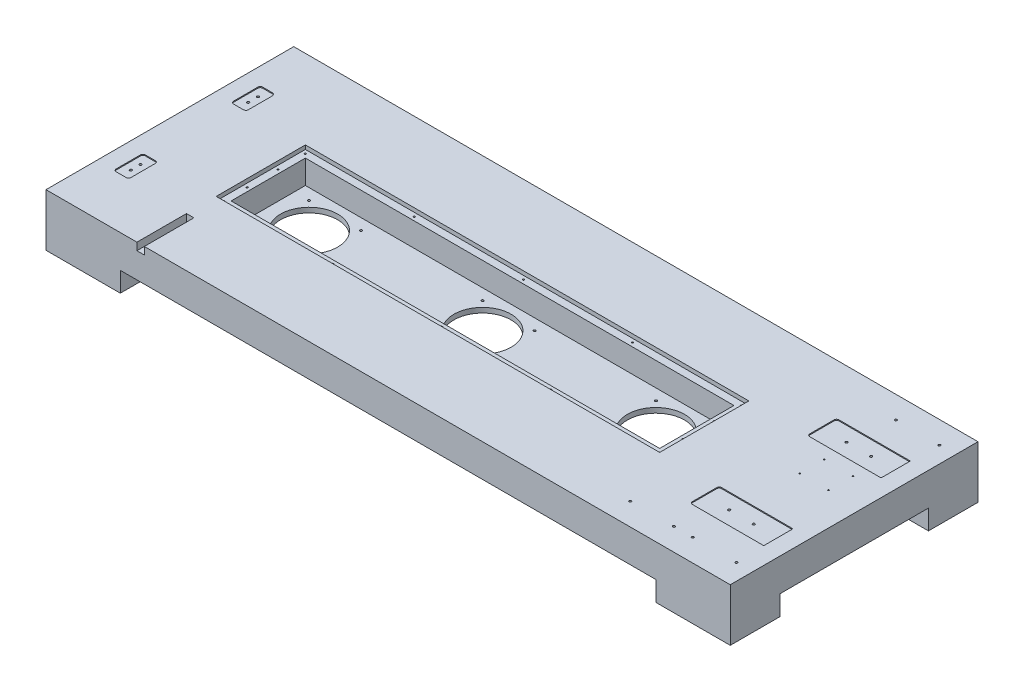
SolidWorks part; units mm, degrees
ref_plane "Front Plane" through (0, 0, 0) normal (0, 0, 1) x (1, 0, 0)
ref_plane "Top Plane" through (0, 0, 0) normal (0, 1, 0) x (1, 0, 0)
ref_plane "Right Plane" through (0, 0, 0) normal (1, 0, 0) x (0, 0, -1)
sketch "Sketch1" plane through (0, 0, 0) normal (0, 1, 0) x (1, 0, 0)
  line L1 (-750, 250) -> (750, 250)
  line L2 (-750, 250) -> (-750, -250)
  line L3 (-750, -250) -> (750, -250)
  line L4 (750, 250) -> (750, -250)
  line L5 (-750, 250) -> (750, -250) construction
  line L6 (-750, -250) -> (750, 250) construction
  point P0 (0, 0)
  dimension "D1" = 1500
  dimension "D2" = 500
sketch "Sketch19" plane through (0, 0, 0) normal (0, 1, 0) x (1, 0, 0)
  line L2 (-447.5, 90) -> (-447.5, -90)
  line L4 (-432.5, 75) -> (-432.5, -75)
  line L6 (-432.5, -75) -> (432.5, -75)
  line L8 (-447.5, -90) -> (447.5, -90)
  line L10 (-447.5, 90) -> (447.5, 90)
  line L12 (-432.5, 75) -> (432.5, 75)
  line L14 (0, 90) -> (0, -90) construction
  line L16 (432.5, 75) -> (432.5, -75)
  line L18 (447.5, 90) -> (447.5, -90)
  point P3 (-432.5, 0)
  dimension "D1" = 15
  dimension "D2" = 15
  dimension "D3" = 15
  dimension "D4" = 15
  dimension "D5" = 865
  dimension "D6" = 150
extrude "Boss-Extrude2" add sketch "Sketch19" along normal blind 48 separate body
sketch "Sketch22" plane through (0, 0, 0) normal (0, 1, 0) x (1, 0, 0)
  line L1 (-447.5, 90) -> (447.5, 90)
  line L2 (-447.5, 90) -> (-447.5, -90)
  line L3 (-447.5, -90) -> (447.5, -90)
  line L4 (447.5, 90) -> (447.5, -90)
  line L5 (-447.5, 90) -> (447.5, -90) construction
  line L6 (-447.5, -90) -> (447.5, 90) construction
extrude "Boss-Extrude3" add sketch "Sketch22" against normal blind 10
sketch "Sketch23" plane through (0, 0, 0) normal (0, 1, 0) x (1, 0, 0)
  line L0 (-447.5, -90) -> (447.5, -90) construction
  line L1 (-750, 250) -> (750, 250)
  line L2 (-750, 250) -> (-750, -250)
  line L3 (-750, -250) -> (750, -250)
  line L4 (750, 250) -> (750, -250)
  line L5 (-447.5, 90) -> (-447.5, -90) construction
  line L6 (447.5, 90) -> (-447.5, 90) construction
  line L7 (447.5, -90) -> (447.5, 90) construction
  line L8 (-447.5, -90) -> (447.5, -90)
  line L9 (-447.5, 90) -> (-447.5, -90)
  line L10 (447.5, 90) -> (-447.5, 90)
  line L11 (447.5, -90) -> (447.5, 90)
extrude "Boss-Extrude4" add sketch "Sketch23" along normal offset from surface 8 and the other way up to surface (10 mm away) up to face at (0, 48, 0) offset beyond the face yes other way up to face at (0, -10, 0)
sketch "Sketch25" plane through (0, 0, 0) normal (0, -1, 0) x (1, 0, 0)
  line L0 (376.7104, 95) -> (506.8132, 123.2951) construction
  line L1 (376.7104, 133.9838) -> (510.7651, 84.6333) construction
  line L6 (-447.5, 90) -> (447.5, 90) construction
  line L8 (521.7058, 80.9826) -> (521.6427, 137.9826)
  line L9 (376.7104, 90) -> (520.9741, 90)
  line L10 (371.7104, 133.9838) -> (371.7104, 95)
  line L11 (520.6818, 138.8932) -> (376.6818, 138.9837)
  arc A0 (371.7104, 95) -> (376.7104, 90) centre (376.7104, 95) ccw
  arc A8 (520.9741, 90) -> (521.7058, 80.9826) centre (510.7651, 84.6333) ccw
  arc A10 (376.6818, 138.9837) -> (371.7104, 133.9838) centre (376.7104, 133.9838) ccw
  arc A11 (521.6427, 137.9826) -> (520.6818, 138.8932) centre (506.8132, 123.2951) ccw
  point P2 (443.2788, 109.4775)
  dimension "D5" = 5
  dimension "D2" = 5
  dimension "D1" = 144
  dimension "D4" = 57
sketch "Sketch26" plane through (0, 0, 0) normal (0, 1, 0) x (1, 0, 0)
  line L0 (-432.5, -75) -> (-447.5, -90) construction
  line L1 (-447.5, 90) -> (-432.5, 75) construction
  line L2 (432.5, -75) -> (447.5, -90) construction
  line L5 (432.5, 75) -> (447.5, 90) construction
  circle A2 centre (-440, -82.5) radius 1.65
  circle A3 centre (-440, 82.5) radius 1.65
  point P4 (-440, -82.5)
  point P15 (440, -82.5)
  point P16 (440, 82.5)
  dimension "D1" = 3.3
  dimension "D3" = 3.3
extrude "Cut-Extrude6" cut sketch "Sketch26" against normal blind 20 from surface at 48 starting at face at (0, 48, 0)
pattern_linear "LPattern1" count 5 spacing 220 along (1, 0, 0) of "Cut-Extrude6"
sketch "Sketch27" plane through (0, 0, 0) normal (0, 1, 0) x (1, 0, 0)
  line L0 (-432.5, 0) -> (-447.5, 0) construction
  line L1 (-432.5, 75) -> (-432.5, -75) construction
  line L2 (-447.5, -90) -> (-447.5, 90) construction
  line L3 (0, -55) -> (0, 55) construction
  line L6 (-440, 90) -> (-440, -90) construction
  line L7 (-447.5, 90) -> (447.5, 90) construction
  line L8 (-447.5, -90) -> (447.5, -90) construction
  line L9 (-504.8814, 84.3322) -> (-440, 84.15) construction
  line L10 (-440, 84.15) -> (-440, 90) construction
  line L11 (440, 84.15) -> (440, 90) construction
  line L12 (504.8814, 84.3322) -> (440, 84.15) construction
  line L13 (440, 90) -> (440, -90) construction
  line L14 (432.5, 0) -> (447.5, 0) construction
  circle A2 centre (-440, 27.5) radius 1.65
  circle A3 centre (-440, -35) radius 1.65
  circle A4 centre (-440, 82.5) radius 1.65 construction
  circle A5 centre (-440, 82.5) radius 1.65 construction
  circle A6 centre (440, -35) radius 1.65
  circle A7 centre (440, 27.5) radius 1.65
  dimension "D5" = 3.3
  dimension "D6" = 3.3
  dimension "D3" = 62.5
  dimension "D4" = 62.5
sketch "Sketch28" plane through (0, 0, 0) normal (0, 1, 0) x (1, 0, 0)
  line L0 (0, 0) -> (57.7, 0) construction
  line L1 (-52.5, 52.5) -> (52.5, 52.5) construction
  line L2 (-52.5, 52.5) -> (-52.5, -52.5) construction
  line L3 (-52.5, -52.5) -> (52.5, -52.5) construction
  line L4 (52.5, 52.5) -> (52.5, -52.5) construction
  line L5 (-52.5, 52.5) -> (52.5, -52.5) construction
  line L6 (-52.5, -52.5) -> (52.5, 52.5) construction
  circle A0 centre (-52.5, 52.5) radius 2.3
  circle A1 centre (52.5, 52.5) radius 2.3
  circle A2 centre (52.5, -52.5) radius 2.3
  circle A3 centre (-52.5, -52.5) radius 2.3
  circle A4 centre (0, 0) radius 57.7
  point P2 (0, 0)
  dimension "D3" = 4.6
  dimension "D4" = 4.6
  dimension "D5" = 4.6
  dimension "D6" = 4.6
  dimension "D7" = 57.7
  dimension "D1" = 105
  dimension "D2" = 105
extrude "Cut-Extrude7" cut sketch "Sketch28" against normal through all both and the other way through all
pattern_linear "LPattern2" count 2 spacing 350 along (-1, 0, 0) count 2 spacing 350 along (1, 0, 0) of "Cut-Extrude7"
extrude "Cut-Extrude8" cut sketch "Sketch27" against normal blind 20 from surface at 48 starting at face at (220, 48, -84.15)
sketch "Sketch30" plane through (0, 0, 0) normal (0, -1, 0) x (1, 0, 0)
  line L0 (566.5, -147.92) -> (715.5, -88.92) construction
  line L1 (566.5, -88.92) -> (715.5, -147.92) construction
  line L2 (566.5, -93.92) -> (566.5, -88.92) construction
  line L3 (566.5, -88.92) -> (571.5, -88.92) construction
  line L4 (571.5, -147.92) -> (566.5, -147.92) construction
  line L5 (566.5, -147.92) -> (566.5, -142.92) construction
  line L6 (571.5, -147.92) -> (714.5, -147.92)
  line L7 (0, 0) -> (750, 0) construction
  line L8 (715.5, -146.92) -> (715.5, -89.92)
  line L10 (566.5, -93.92) -> (566.5, -142.92)
  line L11 (714.5, -88.92) -> (571.5, -88.92)
  line L12 (750, -250) -> (750, 250) construction
  line L14 (0, 0) -> (0, -118.42) construction
  line L15 (566.5, -118.42) -> (0, -118.42) construction
  arc A0 (715.5, -89.92) -> (714.5, -88.92) centre (714.5, -89.92) ccw
  arc A1 (714.5, -147.92) -> (715.5, -146.92) centre (714.5, -146.92) ccw
  arc A9 (566.5, -142.92) -> (571.5, -147.92) centre (571.5, -142.92) ccw
  arc A10 (571.5, -88.92) -> (566.5, -93.92) centre (571.5, -93.92) ccw
  dimension "D1" = 5
  dimension "D2" = 5
  dimension "D5" = 88.92
  dimension "D6" = 566.5
  dimension "D3" = 1
  dimension "D4" = 49
  dimension "D8" = 144
extrude "Cut-Extrude9" cut sketch "Sketch30" along normal blind 2 from surface at -56 starting at face at (0, 56, 0)
mirror "Mirror1" about plane through (0, 0, 0) normal (0, 0, 1) of "Cut-Extrude9"
sketch "Sketch32" plane through (0, 0, 0) normal (0, 1, 0) x (1, 0, 0)
  line L4 (-566.5, 118.42) -> (566.5, 118.42) construction
  line L5 (-591.5, 147.92) -> (-571.5, 147.92)
  line L6 (-596.5, 142.92) -> (-596.5, 93.92)
  line L7 (-591.5, 88.92) -> (-571.5, 88.92)
  line L8 (-566.5, 142.92) -> (-566.5, 93.92)
  line L9 (566.5, 93.92) -> (566.5, 142.92) construction
  arc A4 (-566.5, 142.92) -> (-571.5, 147.92) centre (-571.5, 142.92) ccw
  arc A5 (-566.5, 93.92) -> (-571.5, 88.92) centre (-571.5, 93.92) cw
  arc A6 (-596.5, 93.92) -> (-591.5, 88.92) centre (-591.5, 93.92) ccw
  arc A7 (-596.5, 142.92) -> (-591.5, 147.92) centre (-591.5, 142.92) cw
  point P6 (-566.5, 147.92)
  point P11 (-596.5, 88.92)
  point P14 (-596.5, 147.92)
  dimension "D2" = 20
  dimension "D3" = 5
  dimension "D1" = 49
  dimension "D4" = 1133
extrude "Cut-Extrude10" cut sketch "Sketch32" against normal blind 2 from surface at 56 starting at face at (0, 56, 0)
mirror "Mirror2" about plane through (0, 0, 0) normal (0, 0, 1) of "Cut-Extrude10"
sketch "Sketch33" plane through (0, 0, 0) normal (0, 1, 0) x (1, 0, 0)
  line L0 (-581.5, 147.92) -> (-581.5, 88.92) construction
  line L1 (-571.5, 147.92) -> (-591.5, 147.92) construction
  line L2 (-591.5, 88.92) -> (-571.5, 88.92) construction
  line L3 (-581.5, -88.92) -> (-581.5, -147.92) construction
  line L4 (-591.5, -88.92) -> (-571.5, -88.92) construction
  line L5 (-571.5, -147.92) -> (-591.5, -147.92) construction
  line L6 (566.5, 118.42) -> (715.5, 118.42) construction
  line L7 (566.5, 93.92) -> (566.5, 142.92) construction
  line L8 (715.5, 146.92) -> (715.5, 89.92) construction
  line L9 (566.5, -118.42) -> (715.5, -118.42) construction
  line L10 (566.5, -93.92) -> (566.5, -142.92) construction
  line L11 (715.5, -146.92) -> (715.5, -89.92) construction
  circle A0 centre (-581.5, 108.58) radius 2.35
  circle A1 centre (-581.5, -108.59) radius 2.35
  circle A2 centre (-581.5, 128.25) radius 2.35
  circle A3 centre (-581.5, -128.26) radius 2.35
  circle A4 centre (616.17, -118.42) radius 2.35
  circle A5 centre (665.84, -118.42) radius 2.35
  circle A6 centre (616.17, 118.42) radius 2.35
  circle A7 centre (665.84, 118.42) radius 2.35
  dimension "D1" = 4.7
  dimension "D2" = 4.7
  dimension "D3" = 4.7
  dimension "D8" = 4.7
  dimension "D11" = 4.7
  dimension "D12" = 4.7
  dimension "D13" = 4.7
  dimension "D14" = 4.7
  dimension "D4" = 19.67
  dimension "D5" = 19.67
  dimension "D6" = 19.67
  dimension "D7" = 19.67
  dimension "D9" = 49.67
  dimension "D10" = 49.67
extrude "Cut-Extrude11" cut sketch "Sketch33" against normal through all both and the other way through all
sketch "Sketch34" plane through (0, 0, 0) normal (0, 1, 0) x (1, 0, 0)
  line L0 (-596.5, -118.42) -> (-631, -118.42) construction
  line L1 (-596.5, -142.92) -> (-596.5, -93.92) construction
  line L2 (750, -250) -> (-750, -250) construction
  line L3 (-631, -250) -> (-821.8308, -250)
  line L4 (-631, -250) -> (-631, 290.53)
  line L5 (-631, 290.53) -> (-821.8308, 290.53)
  line L6 (-821.8308, -250) -> (-821.8308, 290.53)
  dimension "D1" = 34.5
extrude "Cut-Extrude12" cut sketch "Sketch34" along normal through all both and the other way through all
sketch "Sketch29" plane through (0, 0, 0) normal (0, 1, 0) x (1, 0, 0)
  line L1 (-631, -250) -> (-481, -250)
  line L2 (-631, -250) -> (-631, -150)
  line L3 (-631, -150) -> (-481, -150)
  line L4 (-481, -250) -> (-481, -150)
  line L5 (-631, 250) -> (-481, 250)
  line L6 (-631, 250) -> (-631, 150)
  line L7 (-631, 150) -> (-481, 150)
  line L8 (-481, 250) -> (-481, 150)
  line L9 (750, -250) -> (600, -250)
  line L10 (750, -250) -> (750, -150)
  line L11 (750, -150) -> (600, -150)
  line L12 (600, -250) -> (600, -150)
  line L13 (750, 250) -> (600, 250)
  line L14 (750, 250) -> (750, 150)
  line L15 (750, 150) -> (600, 150)
  line L16 (600, 250) -> (600, 150)
  dimension "D1" = 150
  dimension "D2" = 100
  dimension "D3" = 150
  dimension "D4" = 100
  dimension "D5" = 150
  dimension "D6" = 100
  dimension "D7" = 100
  dimension "D8" = 150
extrude "Boss-Extrude5" add sketch "Sketch29" against normal blind 50
sketch "Sketch35" plane through (0, 0, 0) normal (0, 1, 0) x (1, 0, 0)
  line L0 (750, -250) -> (-631, -250) construction
  line L1 (-447.5, 90) -> (-432.5, 90) construction
  line L2 (-447.5, 90) -> (-447.5, -250) construction
  line L3 (-447.5, -250) -> (-432.5, -250) construction
  line L4 (-432.5, 90) -> (-432.5, -250) construction
  line L5 (-447.5, 90) -> (447.5, 90) construction
  line L6 (447.5, 90) -> (447.5, 75.0032) construction
  line L7 (447.5, 90) -> (447.5, -90) construction
  line L8 (447.5, 75.0032) -> (-447.5, 75.0032) construction
  line L10 (-447.5, -250) -> (-432.5, -250)
  line L11 (-447.5, -250) -> (-447.5, -150)
  line L12 (-447.5, -150) -> (-432.5, -150)
  line L13 (-432.5, -250) -> (-432.5, -150)
  dimension "D1" = 15
  dimension "D2" = 14.9968
  dimension "D3" = 100
extrude "Cut-Extrude13" cut sketch "Sketch35" against normal blind 15 from surface at 56 starting at face at (-581.5, 56, -118.42)
sketch "Sketch36" plane through (0, 56, 0) normal (0, 1, 0) x (-1, 0, 0)
  line L0 (-750, -250) -> (-750, 250) construction
  circle A0 centre (-683.9963, -14.4973) radius 1.3
  circle A1 centre (-683.9963, -63.4973) radius 1.3
  circle A2 centre (-625.9963, -63.4973) radius 1.3
  circle A3 centre (-625.9963, -14.4973) radius 1.3
  dimension "D1" = 66.0037
  dimension "D5" = 58
  dimension "D3" = 49
  dimension "D7" = 58
extrude "Cut-Extrude14" cut sketch "Sketch36" against normal blind 10
sketch "Sketch37" plane through (0, 56, 0) normal (0, 1, 0) x (1, 0, 0)
  line L0 (629.1607, -205) -> (717.1607, -205) construction
  line L1 (750, -250) -> (-432.5, -250) construction
  line L2 (503.1386, -205) -> (591.1386, -205) construction
  line L3 (629.1607, -205) -> (591.1386, -205) construction
  line L4 (629.1607, 205) -> (717.1607, 205) construction
  line L5 (-631, 250) -> (750, 250) construction
  circle A0 centre (717.1607, -205) radius 2.25
  circle A1 centre (629.1607, -205) radius 2.25
  circle A2 centre (591.1386, -205) radius 2.25
  circle A3 centre (503.1386, -205) radius 2.25
  circle A4 centre (717.1607, 205) radius 2.25
  circle A5 centre (629.1607, 205) radius 2.25
  dimension "D1" = 88
  dimension "D2" = 45
  dimension "D6" = 45
  dimension "D3" = 38.022
  dimension "D4" = 88
  dimension "D5" = 88
extrude "Cut-Extrude15" cut sketch "Sketch37" against normal blind 10
sketch "Sketch39" [suppressed] plane through (0, 0, 0) normal (0, 1, 0) x (1, 0, 0)
  line L0 (-581.5, 147.92) -> (643, 147.92) construction
  line L1 (-571.5, 147.92) -> (-591.5, 147.92) construction
  line L3 (571.5, 147.92) -> (714.5, 147.92) construction
